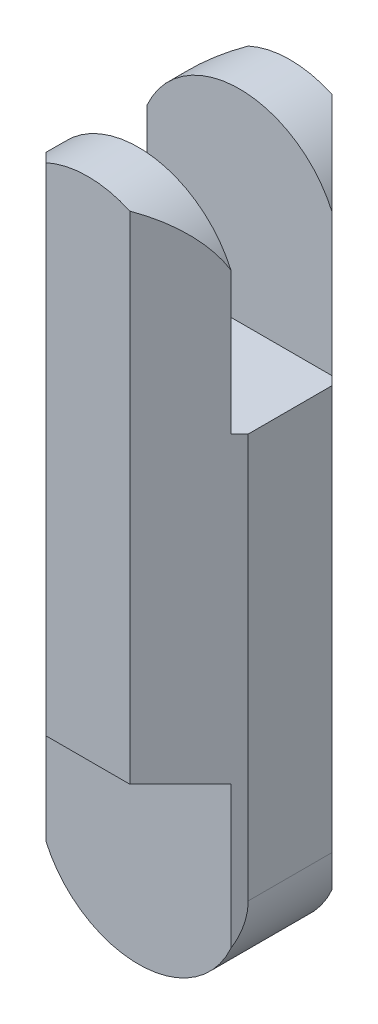
SolidWorks part; units mm, degrees
ref_plane "Front" through (0, 0, 0) normal (0, 0, 1) x (1, 0, 0)
ref_plane "Top" through (0, 0, 0) normal (0, 1, 0) x (1, 0, 0)
ref_plane "Right" through (0, 0, 0) normal (1, 0, 0) x (0, 0, -1)
sketch "草图1" plane through (0, 0, 0) normal (0, 1, 0) x (1, 0, 0)
  line L0 (-12.6518, 0) -> (13.462, 0) construction
  line L1 (0, 11.6722) -> (0, -14.1269) construction
  line L3 (10, 4.1421) -> (4.1421, 10)
  line L4 (4.1421, 10) -> (-4.1421, 10)
  line L5 (-4.1421, 10) -> (-10, 4.1421)
  line L6 (-10, 4.1421) -> (-10, -4.1421)
  line L7 (-10, -4.1421) -> (-4.1421, -10)
  line L8 (-4.1421, -10) -> (4.1421, -10)
  line L9 (4.1421, -10) -> (10, -4.1421)
  line L10 (10, -4.1421) -> (10, 4.1421)
  circle A0 centre (0, 0) radius 10 construction
extrude "凸台-拉伸1" add sketch "草图1" along normal blind 70
sketch "草图2" plane through (0, 0, 10) normal (0, 0, 1) x (1, 0, 0)
  line L0 (0, 0) -> (0, 24) construction
  line L7 (-10, 10) -> (-10, -2.3893)
  line L8 (-10, -2.3893) -> (10, -2.3893)
  line L9 (10, 10) -> (10, -2.3893)
  arc A1 (-10, 10) -> (10, 10) centre (0, 10) ccw
extrude "切除-拉伸1" cut sketch "草图2" against normal blind 66
sketch "草图4" plane through (0, 0, 10) normal (0, 0, 1) x (1, 0, 0)
  line L0 (10, 70) -> (10, 10) construction
  line L2 (-10, 10) -> (-10, 20)
  line L3 (-10, 20) -> (10, 20)
  line L4 (10, 10) -> (10, 20)
  arc A0 (-10, 10) -> (10, 10) centre (0, 10) ccw
extrude "切除-拉伸2" cut sketch "草图4" against normal blind 5
sketch "草图5" plane through (0, 0, -10) normal (0, 0, -1) x (-1, 0, 0)
  line L0 (10, 70) -> (10, 10) construction
  line L2 (-10, 10) -> (-10, 20)
  line L3 (-10, 20) -> (10, 20)
  line L4 (10, 10) -> (10, 20)
  arc A0 (-10, 10) -> (10, 10) centre (0, 10) ccw
extrude "切除-拉伸3" cut sketch "草图5" against normal blind 5
sketch "草图6" plane through (0, 0, 0) normal (0, 0, 1) x (1, 0, 0)
  line L0 (0, 70) -> (0, 0) construction
  line L1 (-4.1421, 70) -> (4.1421, 70) construction
  line L2 (10, 70) -> (10, 10) construction
  line L3 (-10, 70) -> (10, 70)
  line L4 (-10, 70) -> (-10, 50)
  line L5 (-10, 50) -> (10, 50)
  line L6 (10, 70) -> (10, 50)
  dimension "D1" = 20
extrude "切除-拉伸4" cut sketch "草图6" against normal mid plane 10
sketch "草图7" plane through (0, 0, 10) normal (0, 0, 1) x (1, 0, 0)
  line L0 (0, 70) -> (0, 0) construction
  line L1 (-4.1421, 70) -> (4.1421, 70) construction
  line L4 (-10, 60) -> (-10, 79.1079)
  line L5 (-10, 79.1079) -> (10, 79.1079)
  line L6 (10, 60) -> (10, 79.1079)
  arc A0 (10, 60) -> (-10, 60) centre (0, 60) ccw
extrude "切除-拉伸5" cut sketch "草图7" against normal blind 30
